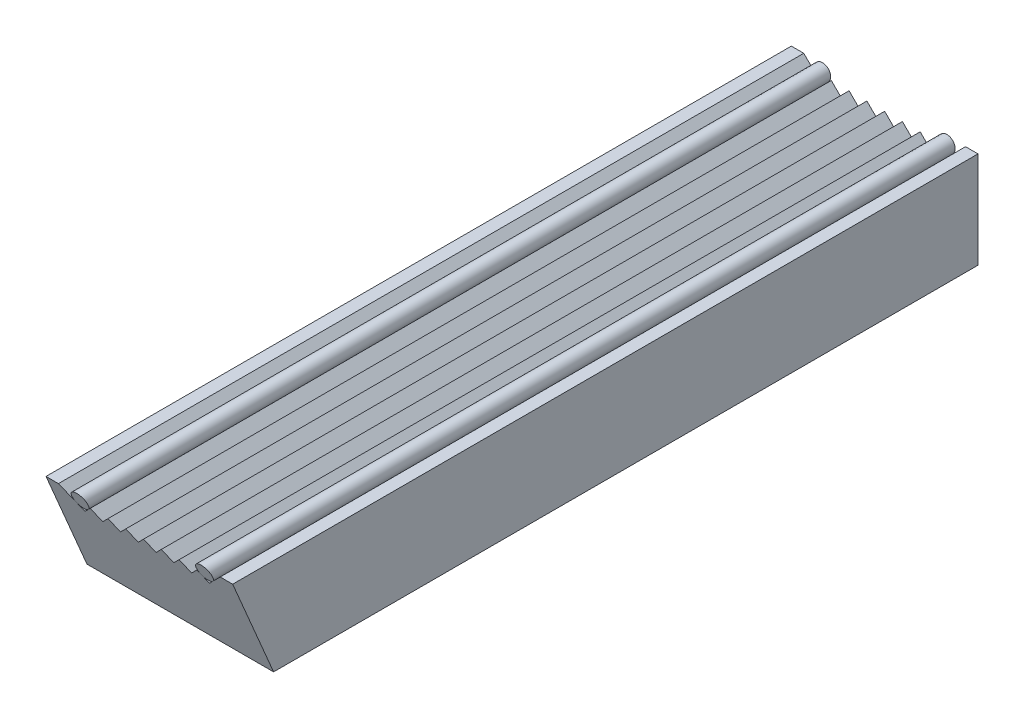
SolidWorks part; units mm, degrees
ref_plane "Front Plane" through (0, 0, 0) normal (0, 0, 1) x (1, 0, 0)
ref_plane "Top Plane" through (0, 0, 0) normal (0, 1, 0) x (1, 0, 0)
ref_plane "Right Plane" through (0, 0, 0) normal (1, 0, 0) x (0, 0, -1)
sketch "Sketch1" plane through (0, 0, 0) normal (0, 0, 1) x (1, 0, 0)
  line L0 (0, 0) -> (0, -1.55)
  line L1 (0, -1.55) -> (3, -1.55)
  line L2 (3, -1.55) -> (3, 0)
  line L20 (3, 0) -> (0, 0)
  dimension "D3" = 3
  dimension "D4" = 1.55
extrude "Boss-Extrude1" add sketch "Sketch1" along normal blind 12
sketch "Sketch2" plane through (0, 0, 12) normal (0, 0, 1) x (1, 0, 0)
  line L0 (0.2, 0) -> (0.5, -0.3)
  line L1 (3, 0) -> (0, 0) construction
  line L2 (0.5, -0.3) -> (0.6429, -0.1571)
  line L3 (0.6429, -0.1571) -> (0.7857, -0.3)
  line L4 (0.7857, -0.3) -> (0.9286, -0.1571)
  line L5 (0.9286, -0.1571) -> (1.0714, -0.3)
  line L6 (1.0714, -0.3) -> (1.2143, -0.1571)
  line L7 (1.2143, -0.1571) -> (1.3571, -0.3)
  line L8 (1.3571, -0.3) -> (1.5, -0.1571)
  line L9 (1.5, -0.1571) -> (1.6429, -0.3)
  line L10 (1.6429, -0.3) -> (1.7857, -0.1571)
  line L11 (1.7857, -0.1571) -> (1.9286, -0.3)
  line L12 (1.9286, -0.3) -> (2.0714, -0.1571)
  line L13 (2.0714, -0.1571) -> (2.2143, -0.3)
  line L14 (2.2143, -0.3) -> (2.3571, -0.1571)
  line L15 (2.3571, -0.1571) -> (2.5, -0.3)
  line L16 (2.5, -0.3) -> (2.8, 0)
  line L17 (2.8, 0) -> (0.2, 0)
  line L18 (0.2, 0) -> (0, 0) construction
  line L19 (2.8, 0) -> (3, 0) construction
  line L20 (0, -1.55) -> (3, -1.55) construction
  dimension "D1" = 0.3
  dimension "D2" = 0.2
  dimension "D3" = 45
extrude "Cut-Extrude1" cut sketch "Sketch2" against normal through all
sketch "Sketch4" plane through (0, 0, 12) normal (0, 0, 1) x (1, 0, 0)
  line L0 (0, 0.02) -> (3, 0.02)
  line L1 (3, 0.02) -> (3, 0.05)
  line L2 (3, 0.05) -> (0, 0.05)
  line L3 (0, 0.05) -> (0, 0.02)
  line L4 (0.2, 0) -> (0, 0) construction
  line L5 (3, -1.55) -> (3, 0) construction
  line L6 (0, 0) -> (0, -1.55) construction
  point P2 (0.1, 0)
  dimension "D1" = 0.05
  dimension "D2" = 0.03
extrude "Boss-Extrude2" add sketch "Sketch4" against normal up to surface (12 mm away) separate body up to face at (1.5, -0.3143, 0)
sketch "Sketch5" plane through (3, 0, 0) normal (1, 0, 0) x (0, 0, -1)
  line L0 (-12, 0.05) -> (-11.3208, -1.55)
  line L1 (-12, -1.55) -> (0, -1.55) construction
  line L2 (-11.3208, -1.55) -> (-12, -1.55)
  line L3 (-12, -1.55) -> (-12, 0.05)
  dimension "D1" = 23
extrude "Cut-Extrude2" cut sketch "Sketch5" against normal through all
sketch "Sketch6" plane through (0, 0, 0) normal (0, 0, -1) x (-1, 0, 0)
  line L0 (-2.5, -0.3) -> (-2.8, 0) construction
  line L2 (-2.3571, -0.1571) -> (-2.5, -0.3) construction
  line L3 (-3, 0.02) -> (0, 0.02) construction
  line L4 (-0.5, -0.3) -> (-0.6429, -0.1571) construction
  line L5 (-0.2, 0) -> (-0.5, -0.3) construction
  circle A0 centre (-2.5, -0.1125) radius 0.1325
  circle A1 centre (-0.5, -0.1125) radius 0.1325
extrude "Boss-Extrude3" add sketch "Sketch6" against normal up to surface (11.931 mm away) separate body
sketch "Sketch7" plane through (0, 0, 0) normal (0, 0, -1) x (-1, 0, 0)
  line L4 (0, 0.02) -> (0, 0.05)
  line L5 (0, 0.05) -> (-3, 0.05)
  line L6 (-3, 0.05) -> (-3, 0.02)
  line L7 (-3, 0.02) -> (0, 0.02)
  line L8 (0, 0.02) -> (0, 0.05)
  line L9 (0, 0.05) -> (-3, 0.05)
  line L10 (-3, 0.05) -> (-3, 0.02)
  line L11 (-3, 0.02) -> (0, 0.02)
  dimension "D1" = 0
extrude "Cut-Extrude3" cut sketch "Sketch7" against normal through all
